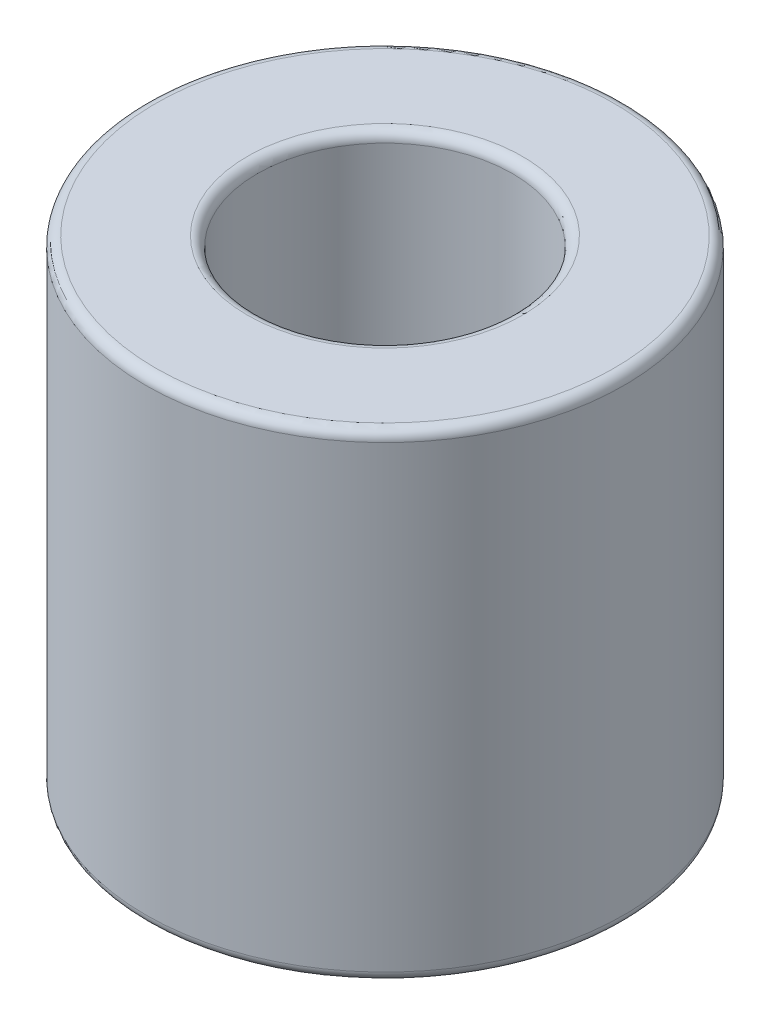
SolidWorks part; units mm, degrees
material "Cast Alloy Steel"
ref_plane "Front Plane" through (0, 0, 0) normal (0, 0, 1) x (1, 0, 0)
ref_plane "Top Plane" through (0, 0, 0) normal (0, 1, 0) x (1, 0, 0)
ref_plane "Right Plane" through (0, 0, 0) normal (1, 0, 0) x (0, 0, -1)
sketch "Sketch1" plane through (0, 0, 0) normal (0, 1, 0) x (1, 0, 0)
  circle A0 centre (0, 0) radius 1.6
  circle A1 centre (0, 0) radius 3
  dimension "D1" = 3.2
  dimension "D2" = 6
extrude "Boss-Extrude1" add sketch "Sketch1" along normal blind 6
fillet "Fillet1" radius 0.125 4 edges at (0, 0, 1.6) (0, 6, 1.6) (0, 0, 3) (0, 6, 3)
